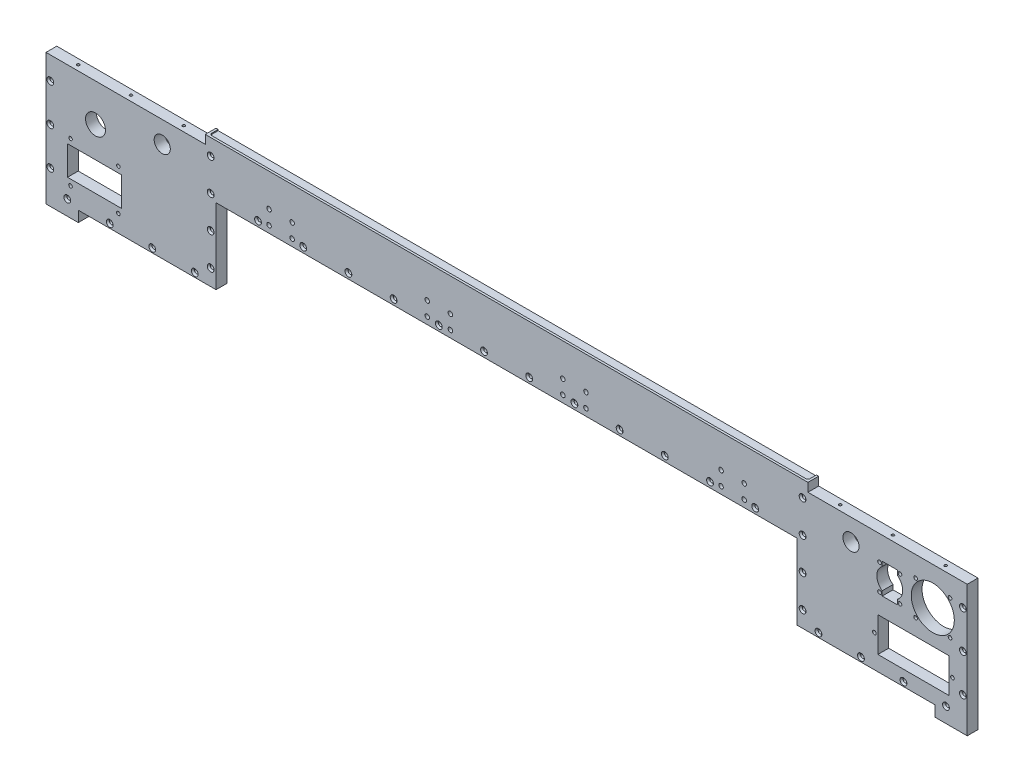
SolidWorks part; units mm, degrees
ref_plane "Front Plane" through (0, 0, 0) normal (0, 0, 1) x (1, 0, 0)
ref_plane "Top Plane" through (0, 0, 0) normal (0, 1, 0) x (1, 0, 0)
ref_plane "Right Plane" through (0, 0, 0) normal (1, 0, 0) x (0, 0, -1)
sketch "Sketch1" plane through (0, 0, 0) normal (0, 0, 1) x (1, 0, 0)
  line L0 (270, 0) -> (-270, 0)
  line L1 (-270, 0) -> (-270, -70)
  line L2 (-270, -70) -> (-398, -70)
  line L3 (-398, -70) -> (-398, -80)
  line L4 (-398, -80) -> (-428, -80)
  line L5 (-428, -80) -> (-428, 42)
  line L7 (0, 50) -> (0, 0) construction
  line L9 (398, -80) -> (428, -80)
  line L10 (398, -70) -> (398, -80)
  line L11 (270, -70) -> (398, -70)
  line L12 (270, 0) -> (270, -70)
  line L13 (-428, 42) -> (-280, 42)
  line L14 (-280, 42) -> (-280, 50)
  line L15 (-280, 50) -> (280, 50)
  line L16 (428, -80) -> (428, 42)
  line L17 (280, 42) -> (280, 50)
  line L18 (428, 42) -> (280, 42)
  point P17 (-280, 46)
  dimension "D1" = 540
  dimension "D2" = 42
  dimension "D3" = 70
  dimension "D4" = 10
  dimension "D5" = 158
  dimension "D6" = 30
  dimension "D7" = 50
  dimension "D8" = 10
extrude "Boss-Extrude1" add sketch "Sketch1" along normal blind 10
sketch "Sketch2" plane through (0, 42, 0) normal (0, 1, 0) x (1, 0, 0)
  circle A0 centre (-305, -5) radius 1.7 construction
  circle A1 centre (-354, -5) radius 1.7 construction
  circle A2 centre (-403, -5) radius 1.7 construction
  circle A3 centre (-305, -5) radius 1.7
  circle A4 centre (-354, -5) radius 1.7
  circle A5 centre (-403, -5) radius 1.7
  point P0 (-305, -5)
  point P2 (-354, -5)
  point P4 (-403, -5)
hole_wizard "M3x0.5 Tapped Hole1" positions "3DSketch1" profile "Sketch4" tap size "M3x0.5" standard "BSI"
sketch3d "3DSketch1"
  point P0 (-403, 42, 5)
  point P3 (-354, 42, 5)
  point P6 (-305, 42, 5)
sketch "Sketch4" plane through (-403, 42, 5) normal (1, 0, 0) x (0, 0, 1)
  line L0 (0, 0) -> (0, 12.2511)
  line L1 (0, 12.2511) -> (1.25, 11.5)
  line L2 (1.25, 11.5) -> (1.25, 0)
  line L5 (1.25, 0) -> (0, 0)
  line L10 (0, 12.2511) -> (-1.25, 11.5) construction
  line L11 (0, -6.35) -> (0, 107.95) construction
  dimension "Tap Drill Dia." = 2.5
  dimension "Tap Drill Depth" = 11.5
  dimension "Drill Angle" = 118
cosmetic thread "Hole Thread1" parameters "D1"=10, "D2"=3
cosmetic thread "Hole Thread2" parameters "D1"=10, "D2"=3
cosmetic thread "Hole Thread3" parameters "D1"=10, "D2"=3
sketch "Sketch5" plane through (0, 0, 10) normal (0, 0, 1) x (1, 0, 0)
  line L0 (-270, -66) -> (-428, -66) construction
  line L1 (-270, -70) -> (-270, 0) construction
  line L2 (-428, 42) -> (-428, -80) construction
  line L3 (-398, -70) -> (-270, -70) construction
  line L4 (-349, -66) -> (-349, -70) construction
  point P8 (-408.25, -66)
  point P9 (-368.75, -66)
  point P12 (-329.25, -66)
  point P13 (-289.75, -66)
  dimension "D1" = 4
  dimension "D2" = 39.5
  dimension "D3" = 19.75
hole_wizard "CSK for M3 Countersunk Flat Head1" positions "3DSketch2" profile "Sketch6" countersink size "M3" standard "BSI"
sketch3d "3DSketch2"
  point P0 (-408.25, -66, 10)
  point P3 (-368.75, -66, 10)
  point P6 (-329.25, -66, 10)
  point P9 (-289.75, -66, 10)
sketch "Sketch6" plane through (-408.25, -66, 10) normal (1, 0, 0) x (0, -1, 0)
  line L0 (0, 0) -> (0, 12.5215)
  line L1 (0, 12.5215) -> (1.7, 11.5)
  line L2 (1.7, 11.5) -> (1.7, 1.45)
  line L3 (1.7, 1.45) -> (3.15, 0)
  line L5 (3.15, 0) -> (0, 0)
  line L6 (-1.7, 1.45) -> (-3.15, 0) construction
  line L10 (0, 12.5215) -> (-1.7, 11.5) construction
  line L11 (0, -6.35) -> (0, 107.95) construction
  dimension "Hole Dia." = 3.4
  dimension "Hole Depth" = 11.5
  dimension "Near C'Sink Dia." = 6.3
  dimension "Near C'Sink Angle" = 90
  dimension "Drill Angle" = 118
sketch "Sketch7" plane through (0, 0, 10) normal (0, 0, 1) x (1, 0, 0)
  line L0 (-424, 42) -> (-424, -70) construction
  line L1 (-280, 42) -> (-428, 42) construction
  line L2 (-424, -70) -> (-398, -70) construction
  line L3 (-428, 42) -> (-428, -80) construction
  point P8 (-424, -14)
  point P9 (-424, 21)
  point P10 (-424, -49)
  dimension "D1" = 4
  dimension "D2" = 35
  dimension "D3" = 35
hole_wizard "CSK for M3 Countersunk Flat Head2" positions "3DSketch3" profile "Sketch8" countersink size "M3" standard "BSI"
sketch3d "3DSketch3"
  point P0 (-424, 21, 10)
  point P3 (-424, -14, 10)
  point P6 (-424, -49, 10)
sketch "Sketch8" plane through (-424, 21, 10) normal (1, 0, 0) x (0, -1, 0)
  line L0 (0, 0) -> (0, 12.5215)
  line L1 (0, 12.5215) -> (1.7, 11.5)
  line L2 (1.7, 11.5) -> (1.7, 1.45)
  line L3 (1.7, 1.45) -> (3.15, 0)
  line L5 (3.15, 0) -> (0, 0)
  line L6 (-1.7, 1.45) -> (-3.15, 0) construction
  line L10 (0, 12.5215) -> (-1.7, 11.5) construction
  line L11 (0, -6.35) -> (0, 107.95) construction
  dimension "Hole Dia." = 3.4
  dimension "Hole Depth" = 11.5
  dimension "Near C'Sink Dia." = 6.3
  dimension "Near C'Sink Angle" = 90
  dimension "Drill Angle" = 118
sketch "Sketch10" plane through (0, 0, 10) normal (0, 0, 1) x (1, 0, 0)
  line L0 (-275, 50) -> (-275, -70) construction
  line L1 (280, 50) -> (-280, 50) construction
  line L2 (-398, -70) -> (-270, -70) construction
  line L3 (-270, -70) -> (-270, 0) construction
  line L5 (-275, -10) -> (-270, -10) construction
  point P8 (-275, 35)
  point P9 (-275, -25)
  point P11 (-275, -55)
  point P12 (-275, -10)
  point P13 (-275, 5)
  dimension "D1" = 5
  dimension "D2" = 15
  dimension "D3" = 30
hole_wizard "CSK for M3 Countersunk Flat Head3" positions "3DSketch4" profile "Sketch11" countersink size "M3" standard "BSI"
sketch3d "3DSketch4"
  point P0 (-275, 35, 10)
  point P3 (-275, 5, 10)
  point P6 (-275, -25, 10)
  point P9 (-275, -55, 10)
sketch "Sketch11" plane through (-275, 35, 10) normal (1, 0, 0) x (0, -1, 0)
  line L0 (0, 0) -> (0, 12.5215)
  line L1 (0, 12.5215) -> (1.7, 11.5)
  line L2 (1.7, 11.5) -> (1.7, 1.45)
  line L3 (1.7, 1.45) -> (3.15, 0)
  line L5 (3.15, 0) -> (0, 0)
  line L6 (-1.7, 1.45) -> (-3.15, 0) construction
  line L10 (0, 12.5215) -> (-1.7, 11.5) construction
  line L11 (0, -6.35) -> (0, 107.95) construction
  dimension "Hole Dia." = 3.4
  dimension "Hole Depth" = 11.5
  dimension "Near C'Sink Dia." = 6.3
  dimension "Near C'Sink Angle" = 90
  dimension "Drill Angle" = 118
sketch "Sketch12" plane through (0, 0, 10) normal (0, 0, 1) x (1, 0, 0)
  line L0 (-270, 5) -> (270, 5) construction
  line L1 (270, 0) -> (270, -70) construction
  line L2 (-270, -70) -> (-270, 0) construction
  line L3 (-270, 0) -> (270, 0) construction
  point P6 (-63, 5)
  point P7 (-105, 5)
  point P8 (-147, 5)
  point P9 (-189, 5)
  point P10 (-231, 5)
  point P11 (-21, 5)
  dimension "D1" = 21
  dimension "D2" = 42
  dimension "D3" = 42
  dimension "D4" = 42
  dimension "D5" = 42
  dimension "D6" = 42
  dimension "D7" = 5
hole_wizard "CSK for M3 Countersunk Flat Head4" positions "3DSketch5" profile "Sketch13" countersink size "M3" standard "BSI"
sketch3d "3DSketch5"
  point P0 (-231, 5, 10)
  point P3 (-189, 5, 10)
  point P6 (-147, 5, 10)
  point P9 (-105, 5, 10)
  point P12 (-63, 5, 10)
  point P15 (-21, 5, 10)
sketch "Sketch13" plane through (-231, 5, 10) normal (1, 0, 0) x (0, -1, 0)
  line L0 (0, 0) -> (0, 12.5215)
  line L1 (0, 12.5215) -> (1.7, 11.5)
  line L2 (1.7, 11.5) -> (1.7, 1.45)
  line L3 (1.7, 1.45) -> (3.15, 0)
  line L5 (3.15, 0) -> (0, 0)
  line L6 (-1.7, 1.45) -> (-3.15, 0) construction
  line L10 (0, 12.5215) -> (-1.7, 11.5) construction
  line L11 (0, -6.35) -> (0, 107.95) construction
  dimension "Hole Dia." = 3.4
  dimension "Hole Depth" = 11.5
  dimension "Near C'Sink Dia." = 6.3
  dimension "Near C'Sink Angle" = 90
  dimension "Drill Angle" = 118
mirror "Mirror1" about plane through (0, 0, 0) normal (1, 0, 0) of "M3x0.5 Tapped Hole1", "CSK for M3 Countersunk Flat Head1", "CSK for M3 Countersunk Flat Head2", "CSK for M3 Countersunk Flat Head3", "CSK for M3 Countersunk Flat Head4"
sketch "Sketch14" plane through (0, 50, 0) normal (0, 1, 0) x (1, 0, 0)
  line L0 (280, 0) -> (-280, 0) construction
  line L1 (-278, 0) -> (278, 0)
  line L2 (-278, 0) -> (-278, -8)
  line L3 (-278, -8) -> (278, -8)
  line L4 (278, 0) -> (278, -8)
  line L5 (280, -10) -> (280, 0) construction
  line L6 (280, -10) -> (-280, -10) construction
  line L7 (-280, -10) -> (-280, 0) construction
  dimension "D1" = 2
  dimension "D2" = 2
  dimension "D3" = 2
extrude "Cut-Extrude1" cut sketch "Sketch14" against normal blind 1
fillet "Fillet1" radius 2 2 edges at (278, 49.5, 8) (-278, 49.5, 8)
sketch "Sketch17" plane through (0, 0, 10) normal (0, 0, 1) x (1, 0, 0)
  line L0 (270, -70) -> (398, -70) construction
  line L1 (411, -56) -> (345, -56)
  line L2 (411, -56) -> (411, -24)
  line L3 (411, -24) -> (345, -24)
  line L4 (345, -56) -> (345, -24)
  line L5 (411, -56) -> (345, -24) construction
  line L6 (411, -24) -> (345, -56) construction
  line L7 (428, -80) -> (428, 42) construction
  line L8 (341.75, -40) -> (414.25, -40) construction
  line L9 (428, 42) -> (280, 42) construction
  line L10 (412, -9) -> (380, -9) construction
  line L11 (412, -9) -> (412, 23) construction
  line L12 (412, 23) -> (380, 23) construction
  line L13 (380, -9) -> (380, 23) construction
  line L14 (412, -9) -> (380, 23) construction
  line L15 (412, 23) -> (380, -9) construction
  line L16 (349, 16.7468) -> (349, 21)
  line L21 (376, -13) -> (416, -13) construction
  line L22 (376, -13) -> (376, 27) construction
  line L23 (365.5, -5) -> (346.5, -5) construction
  line L24 (365.5, -5) -> (365.5, 19) construction
  line L25 (365.5, 19) -> (346.5, 19) construction
  line L26 (346.5, -5) -> (346.5, 19) construction
  line L27 (365.5, -5) -> (346.5, 19) construction
  line L28 (365.5, 19) -> (346.5, -5) construction
  line L29 (376, 27) -> (416, 27) construction
  line L30 (416, -13) -> (416, 27) construction
  line L31 (376, -13) -> (416, 27) construction
  line L32 (376, 27) -> (416, -13) construction
  line L33 (363, -7) -> (349, -7)
  line L34 (363, -7) -> (363, -2.7468)
  line L35 (363, 21) -> (349, 21)
  line L36 (349, -7) -> (349, -2.7468)
  line L37 (363, -7) -> (349, 21) construction
  line L38 (363, 21) -> (349, -7) construction
  line L39 (363, 16.7468) -> (363, 21)
  circle A0 centre (396, 7) radius 20
  arc A1 (349, 16.7468) -> (349, -2.7468) centre (356, 7) ccw
  arc A2 (363, -2.7468) -> (363, 16.7468) centre (356, 7) ccw
  point P0 (378, -40)
  point P11 (378, -40)
  point P12 (396, 7)
  point P13 (341.75, -40)
  point P14 (414.25, -40)
  point P26 (356, 7)
  dimension "D10" = 40
  dimension "D13" = 24
  dimension "D1" = 32
  dimension "D2" = 66
  dimension "D3" = 30
  dimension "D4" = 50
  dimension "D5" = 72.5
  dimension "D6" = 32
  dimension "D7" = 32
  dimension "D8" = 32
  dimension "D11" = 19
  dimension "D12" = 24
  dimension "D9" = 35
  dimension "D15" = 40
  dimension "D16" = 40
  dimension "D17" = 40
  dimension "D14" = 35
  dimension "D18" = 28
  dimension "D19" = 14
extrude "Cut-Extrude4" cut sketch "Sketch17" against normal through all
hole_wizard "Ø3.4 (3.4) Diameter Hole1" positions "3DSketch7" profile "Sketch20" hole size "Ø3.4" standard "ANSI Metric" end condition through all
sketch3d "3DSketch7"
  point P0 (346.5, 19, 10)
  point P3 (365.5, 19, 10)
  point P6 (365.5, -5, 10)
  point P9 (346.5, -5, 10)
  point P12 (412, 23, 10)
  point P15 (380, 23, 10)
  point P18 (380, -9, 10)
  point P21 (412, -9, 10)
  point P25 (341.75, -40, 10)
  point P28 (414.25, -40, 10)
sketch "Sketch20" plane through (346.5, 19, 10) normal (1, 0, 0) x (0, -1, 0)
  line L0 (0, 0) -> (0, 10)
  line L1 (0, 10) -> (1.7, 10)
  line L2 (1.7, 10) -> (1.7, 0)
  line L5 (1.7, 0) -> (0, 0)
  line L11 (0, -6.35) -> (0, 107.95) construction
  dimension "Thru Hole Dia." = 3.4
  dimension "Thru Hole Depth" = 10
sketch "Sketch21" plane through (0, 0, 10) normal (0, 0, 1) x (1, 0, 0)
  line L0 (-398, -70) -> (-270, -70) construction
  line L1 (-360.775, -54.05) -> (-405.225, -54.05) construction
  line L2 (-360.775, -54.05) -> (-360.775, -15.95) construction
  line L3 (-360.775, -15.95) -> (-405.225, -15.95) construction
  line L4 (-405.225, -54.05) -> (-405.225, -15.95) construction
  line L5 (-360.775, -54.05) -> (-405.225, -15.95) construction
  line L6 (-360.775, -15.95) -> (-405.225, -54.05) construction
  line L7 (-428, 42) -> (-428, -80) construction
  line L9 (-358, -48.5) -> (-408, -48.5)
  line L10 (-358, -48.5) -> (-358, -21.5)
  line L11 (-358, -21.5) -> (-408, -21.5)
  line L12 (-408, -48.5) -> (-408, -21.5)
  line L13 (-358, -48.5) -> (-408, -21.5) construction
  line L14 (-358, -21.5) -> (-408, -48.5) construction
  point P0 (-383, -35)
  point P9 (-383, -35)
  dimension "D1" = 44.45
  dimension "D2" = 38.1
  dimension "D3" = 35
  dimension "D4" = 45
  dimension "D5" = 50
  dimension "D6" = 27
hole_wizard "M4x0.7 Tapped Hole1" positions "3DSketch8" profile "Sketch22" tap size "M4x0.7" standard "ANSI Metric" end condition through all
sketch3d "3DSketch8"
  point P0 (-405.225, -15.95, 10)
  point P3 (-360.775, -15.95, 10)
  point P6 (-360.775, -54.05, 10)
  point P9 (-405.225, -54.05, 10)
sketch "Sketch22" plane through (-405.225, -15.95, 10) normal (1, 0, 0) x (0, -1, 0)
  line L0 (0, 0) -> (0, 10)
  line L1 (0, 10) -> (1.65, 10)
  line L2 (1.65, 10) -> (1.65, 0)
  line L5 (1.65, 0) -> (0, 0)
  line L11 (0, -6.35) -> (0, 107.95) construction
  dimension "Thru Tap Drill Dia." = 3.3
  dimension "Thru Tap Drill Depth" = 10
cosmetic thread "Hole Thread6" parameters "D2"=4
cosmetic thread "Hole Thread7" parameters "D2"=4
cosmetic thread "Hole Thread8" parameters "D2"=4
cosmetic thread "Hole Thread9" parameters "D2"=4
extrude "Cut-Extrude5" cut sketch "Sketch21" against normal through all
sketch "Sketch23" plane through (0, 0, 10) normal (0, 0, 1) x (1, 0, 0)
  line L0 (-73.75, 6.5) -> (-52.25, 6.5) construction
  line L1 (-52.25, 6.5) -> (-52.25, 19.5) construction
  line L2 (-63, 6.5) -> (-63, 0) construction
  line L3 (-73.75, 6.5) -> (-73.75, 19.5) construction
  line L4 (-270, 0) -> (270, 0) construction
  circle A0 centre (-63, 5) radius 1.7 construction
  point P2 (-63, 6.5)
  point P6 (-63, 5)
  point P11 (-63, 5)
  dimension "D1" = 13
  dimension "D2" = 21.5
  dimension "D3" = 6.5
  dimension "D4" = 13
hole_wizard "M5x0.8 Tapped Hole1" positions "3DSketch9" profile "Sketch24" tap size "M5x0.8" standard "BSI" end condition through all
sketch3d "3DSketch9"
  point P0 (-73.75, 19.5, 10)
  point P3 (-73.75, 6.5, 10)
  point P6 (-52.25, 19.5, 10)
  point P9 (-52.25, 6.5, 10)
sketch "Sketch24" plane through (-73.75, 19.5, 10) normal (1, 0, 0) x (0, -1, 0)
  line L0 (0, 0) -> (0, 10)
  line L1 (0, 10) -> (2.1, 10)
  line L2 (2.1, 10) -> (2.1, 0)
  line L5 (2.1, 0) -> (0, 0)
  line L11 (0, -6.35) -> (0, 107.95) construction
  dimension "Thru Tap Drill Dia." = 4.2
  dimension "Thru Tap Drill Depth" = 10
cosmetic thread "Hole Thread10" parameters "D2"=5
cosmetic thread "Hole Thread11" parameters "D2"=5
cosmetic thread "Hole Thread12" parameters "D2"=5
cosmetic thread "Hole Thread13" parameters "D2"=5
pattern_linear "LPattern1" count 2 spacing 147 along (-1, 0, 0) of "M5x0.8 Tapped Hole1"
mirror "Mirror2" about plane through (0, 0, 0) normal (1, 0, 0) of "M5x0.8 Tapped Hole1", "LPattern1"
sketch "Sketch25" plane through (0, 0, 10) normal (0, 0, 1) x (1, 0, 0)
  line L0 (-280, 42) -> (-428, 42) construction
  line L1 (-428, 42) -> (-428, -80) construction
  point P0 (-382, 7)
  dimension "D1" = 35
  dimension "D2" = 46
hole_wizard "M20x1.5 Tapped Hole1" positions "3DSketch10" profile "Sketch26" tap size "M20x1.5" standard "BSI" end condition through all
sketch3d "3DSketch10"
  point P0 (-382, 7, 10)
cosmetic thread "Hole Thread14" parameters "D2"=20
sketch "Sketch26" plane through (-382, 7, 10) normal (1, 0, 0) x (0, -1, 0)
  line L0 (0, 0) -> (0, 10)
  line L1 (0, 10) -> (9.25, 10)
  line L2 (9.25, 10) -> (9.25, 0)
  line L5 (9.25, 0) -> (0, 0)
  line L11 (0, -6.35) -> (0, 107.95) construction
  dimension "Thru Tap Drill Dia." = 18.5
  dimension "Thru Tap Drill Depth" = 10
sketch "Sketch27" plane through (0, 0, 10) normal (0, 0, 1) x (1, 0, 0)
  line L0 (-280, 42) -> (-428, 42) construction
  line L1 (-280, 50) -> (-280, 42) construction
  point P0 (-320, 22)
  dimension "D1" = 20
  dimension "D2" = 40
hole_wizard "Ø15.0 (15) Diameter Hole1" positions "3DSketch11" profile "Sketch28" hole size "Ø15.0" standard "ANSI Metric" end condition through all
sketch3d "3DSketch11"
  point P0 (-320, 22, 10)
sketch "Sketch28" plane through (-320, 22, 10) normal (1, 0, 0) x (0, -1, 0)
  line L0 (0, 0) -> (0, 10)
  line L1 (0, 10) -> (7.5, 10)
  line L2 (7.5, 10) -> (7.5, 0)
  line L5 (7.5, 0) -> (0, 0)
  line L11 (0, -6.35) -> (0, 107.95) construction
  dimension "Thru Hole Dia." = 15
  dimension "Thru Hole Depth" = 10
mirror "Mirror3" about plane through (0, 0, 0) normal (1, 0, 0) of "Ø15.0 (15) Diameter Hole1"
equation "\"D3@Sketch5\"=\"D2@Sketch5\"/2"
equation "\"D6@Sketch12\"=\"D2@Sketch12\""
equation "\"D5@Sketch12\"=\"D2@Sketch12\""
equation "\"D4@Sketch12\"=\"D2@Sketch12\""
equation "\"D3@Sketch12\"=\"D2@Sketch12\""
equation "\"D1@Sketch12\"=\"D2@Sketch12\"/2"
equation "\"D9@Sketch17\"=\"D14@Sketch17\""
